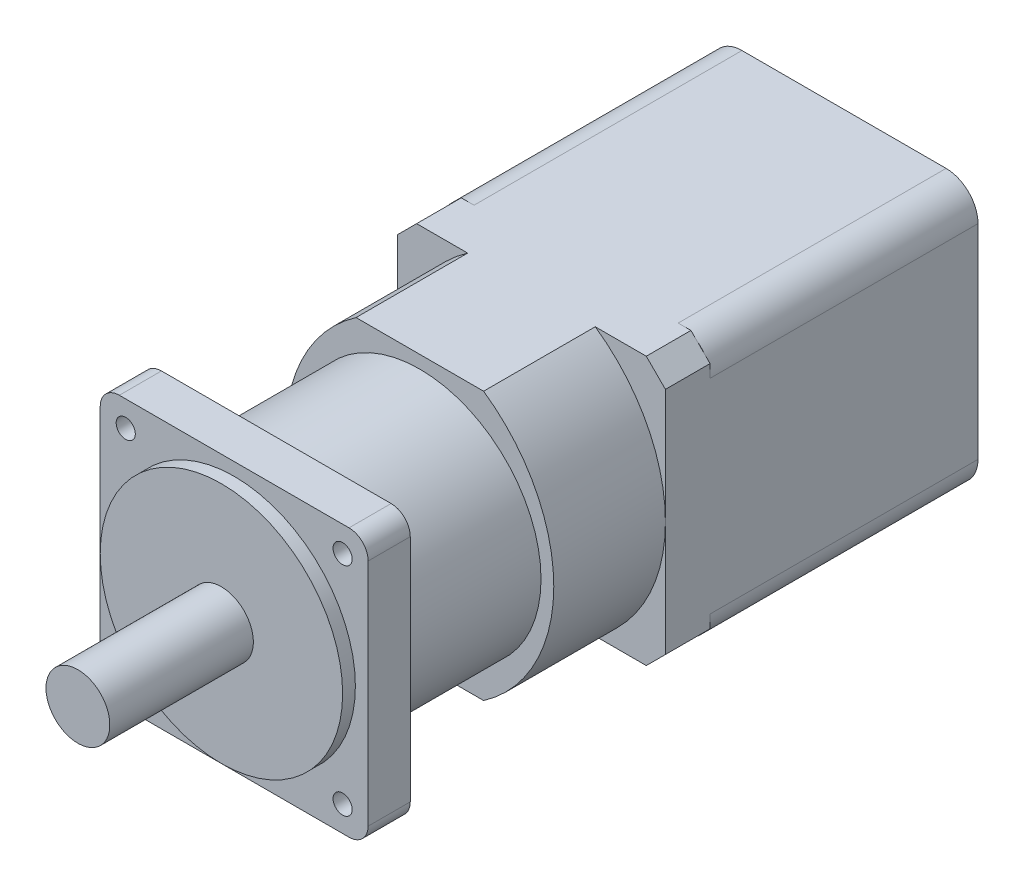
SolidWorks part; units mm, degrees
ref_plane "前视基准面" through (0, 0, 0) normal (0, 0, 1) x (1, 0, 0)
ref_plane "上视基准面" through (0, 0, 0) normal (0, 1, 0) x (1, 0, 0)
ref_plane "右视基准面" through (0, 0, 0) normal (1, 0, 0) x (0, 0, -1)
sketch "草图1" plane through (0, 0, 0) normal (0, 0, 1) x (1, 0, 0)
  line L1 (-16, 21) -> (16, 21)
  line L2 (-21, 16) -> (-21, -16)
  line L3 (-16, -21) -> (16, -21)
  line L4 (21, 16) -> (21, -16)
  line L5 (-21, 21) -> (21, -21) construction
  line L6 (-21, -21) -> (21, 21) construction
  arc A0 (-21, 16) -> (-16, 21) centre (-16, 16) cw
  arc A1 (-16, -21) -> (-21, -16) centre (-16, -16) cw
  arc A2 (16, -21) -> (21, -16) centre (16, -16) ccw
  arc A3 (21, 16) -> (16, 21) centre (16, 16) ccw
  point P0 (0, 0)
  dimension "D2" = 5
  dimension "D1" = 42
extrude "凸台-拉伸1" add sketch "草图1" along normal blind 42
sketch "草图2" plane through (0, 0, 42) normal (0, 0, 1) x (1, 0, 0)
  line L0 (-21, 16) -> (-21, -16) construction
  line L1 (18, 21) -> (-18, 21)
  line L2 (21, 18) -> (21, -18)
  line L3 (18, -21) -> (-18, -21)
  line L4 (-21, 18) -> (-21, -18)
  line L5 (21, 21) -> (-21, -21) construction
  line L6 (21, -21) -> (-21, 21) construction
  line L7 (18, 21) -> (21, 18)
  line L8 (-18, 21) -> (-21, 18)
  line L9 (-18, -21) -> (-21, -18)
  line L10 (21, -18) -> (18, -21)
  point P0 (0, 0)
  dimension "D1" = 3
  dimension "D2" = 45
  dimension "D3" = 3
  dimension "D4" = 45
  dimension "D5" = 3
  dimension "D6" = 45
  dimension "D7" = 3
  dimension "D8" = 45
  dimension "D9" = 42
extrude "凸台-拉伸2" add sketch "草图2" along normal blind 7
sketch "草图3" plane through (0, 0, 49) normal (0, 0, 1) x (1, 0, 0)
  line L0 (-10, 21) -> (10, 21)
  line L1 (-18, -21) -> (18, -21) construction
  line L2 (-10, -21) -> (10, -21)
  line L3 (21, -18) -> (21, 18) construction
  line L4 (18, 21) -> (-18, 21) construction
  line L5 (-21, 18) -> (-21, -18) construction
  arc A0 (-10, -21) -> (-10, 21) centre (4.5455, 0) cw
  arc A1 (10, 21) -> (10, -21) centre (-4.5455, 0) cw
  dimension "D1" = 20
extrude "凸台-拉伸3" add sketch "草图3" along normal blind 17.5
sketch "草图4" plane through (0, 0, 66.5) normal (0, 0, 1) x (1, 0, 0)
  circle A0 centre (0, 0) radius 19
  dimension "D1" = 38
extrude "凸台-拉伸4" add sketch "草图4" along normal blind 22.5
sketch "草图5" plane through (0, 0, 89) normal (0, 0, 1) x (1, 0, 0)
  line L1 (-18, 21) -> (18, 21)
  line L2 (-21, 18) -> (-21, -18)
  line L3 (-18, -21) -> (18, -21)
  line L4 (21, 18) -> (21, -18)
  line L5 (-21, 21) -> (21, -21) construction
  line L6 (-21, -21) -> (21, 21) construction
  arc A0 (18, 21) -> (21, 18) centre (18, 18) cw
  arc A1 (21, -18) -> (18, -21) centre (18, -18) cw
  arc A2 (-18, -21) -> (-21, -18) centre (-18, -18) cw
  arc A3 (-21, 18) -> (-18, 21) centre (-18, 18) cw
  circle A4 centre (-17, 17) radius 1.5
  circle A5 centre (17, 17) radius 1.5
  circle A6 centre (17, -17) radius 1.5
  circle A7 centre (-17, -17) radius 1.5
  point P0 (0, 0)
  point P29 (0, 0)
  dimension "D2" = 3
  dimension "D3" = 3
  dimension "D1" = 42
  dimension "D4" = 4
  dimension "D5" = 4
extrude "凸台-拉伸5" add sketch "草图5" along normal blind 6.6
sketch "草图6" plane through (0, 0, 95.6) normal (0, 0, 1) x (1, 0, 0)
  circle A0 centre (0, 0) radius 19
  dimension "D1" = 38
extrude "凸台-拉伸6" add sketch "草图6" along normal blind 2
sketch "草图7" plane through (0, 0, 97.6) normal (0, 0, 1) x (1, 0, 0)
  circle A0 centre (0, 0) radius 5
  dimension "D1" = 10
extrude "凸台-拉伸7" add sketch "草图7" along normal blind 22.5
